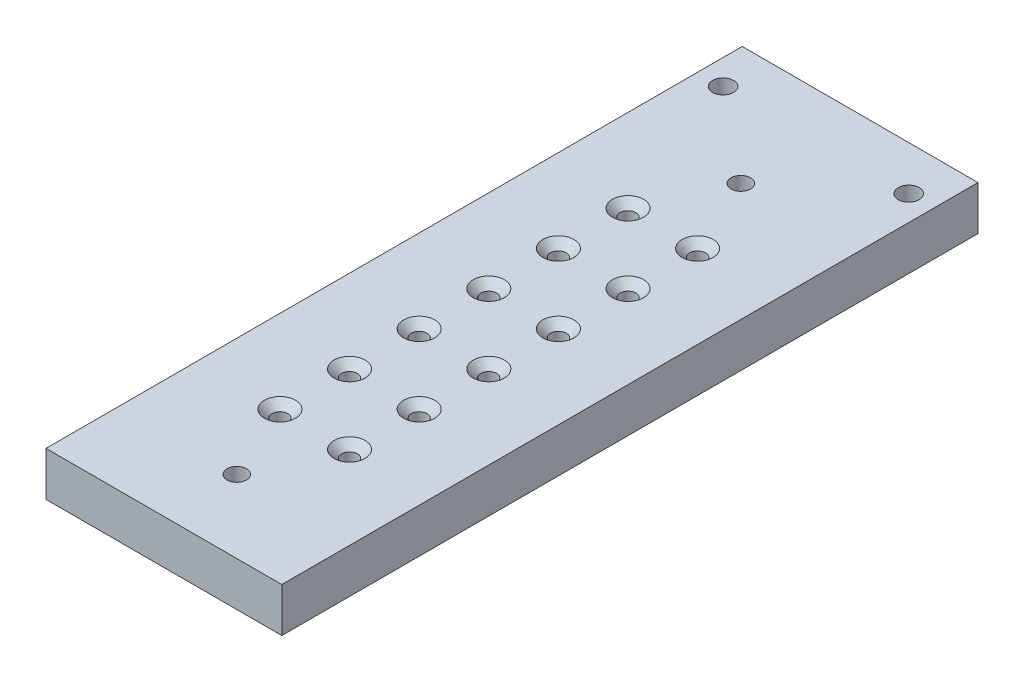
SolidWorks part; units mm, degrees
ref_plane "Front" through (0, 0, 0) normal (0, 0, 1) x (1, 0, 0)
ref_plane "Top" through (0, 0, 0) normal (0, 1, 0) x (1, 0, 0)
ref_plane "Right" through (0, 0, 0) normal (1, 0, 0) x (0, 0, -1)
sketch "Sketch1" plane through (0, 0, 0) normal (0, 0, 1) x (1, 0, 0)
  line L1 (-25.4, -4.7625) -> (25.4, -4.7625)
  line L2 (-25.4, -4.7625) -> (-25.4, 4.7625)
  line L3 (-25.4, 4.7625) -> (25.4, 4.7625)
  line L4 (25.4, -4.7625) -> (25.4, 4.7625)
  line L5 (-25.4, -4.7625) -> (25.4, 4.7625) construction
  line L6 (-25.4, 4.7625) -> (25.4, -4.7625) construction
  point P0 (0, 0)
  dimension "D1" = 50.8
  dimension "D2" = 9.525
extrude "Boss-Extrude1" add sketch "Sketch1" along normal mid plane 150
sketch "Sketch5" plane through (0, 4.7625, 0) normal (0, 1, 0) x (1, 0, 0)
  line L0 (-25.4, -75) -> (-25.4, 75) construction
  line L1 (-21.3194, 50) -> (21.3194, 50)
  line L2 (-21.3194, 50) -> (-21.3194, -60)
  line L3 (-21.3194, -60) -> (21.3194, -60)
  line L4 (21.3194, 50) -> (21.3194, -60)
  line L5 (-25.4, 45.8) -> (25.4, 45.8)
  line L6 (-25.4, 45.8) -> (-25.4, -55.8)
  line L7 (-25.4, -55.8) -> (25.4, -55.8)
  line L8 (25.4, 45.8) -> (25.4, -55.8)
  line L9 (25.4, -75) -> (25.4, 75) construction
  line L10 (25.4, -75) -> (-25.4, -75) construction
  line L12 (-9.525, -55.8) -> (9.525, -55.8)
  line L13 (-9.525, -55.8) -> (-9.525, -70.8)
  line L14 (-9.525, -70.8) -> (9.525, -70.8)
  line L15 (9.525, -55.8) -> (9.525, -70.8)
  line L16 (-25.4, 75) -> (25.4, 75)
  line L17 (-25.4, 75) -> (-25.4, 55.95)
  line L18 (-25.4, 55.95) -> (25.4, 55.95)
  line L19 (25.4, 75) -> (25.4, 55.95)
  point P12 (0, 50)
  point P13 (0, -55.8)
  point P15 (-21.3194, -5)
  point P16 (-25.4, -5)
  point P17 (0, -70.8)
  dimension "D1" = 110
  dimension "D2" = 101.6
  dimension "D3" = 15
  dimension "D4" = 15
  dimension "D5" = 19.05
  dimension "D6" = 19.05
hole_wizard "Tap Drill for M5x0.8 Tap1" positions "Sketch6" profile "Sketch7" hole size "M5x0.8" standard "ANSI Metric" end condition up to next
sketch "Sketch6" plane through (0, 4.7625, 0) normal (0, 1, 0) x (1, 0, 0)
  line L0 (-25.4, -55.8) -> (25.4, -55.8) construction
  line L1 (-25.4, 45.8) -> (25.4, 45.8) construction
  point P0 (0, -59.3)
  point P7 (0, 49.3)
  dimension "D1" = 3.5
  dimension "D2" = 3.5
sketch "Sketch7" plane through (0, 4.7625, 59.3) normal (1, 0, 0) x (0, 0, 1)
  line L0 (0, 0) -> (0, 9.525)
  line L1 (0, 9.525) -> (2.1, 9.525)
  line L2 (2.1, 9.525) -> (2.1, 0)
  line L5 (2.1, 0) -> (0, 0)
  line L11 (0, -6.35) -> (0, 107.95) construction
  dimension "Thru Hole Dia." = 4.2
  dimension "Thru Hole Depth" = 9.525
hole_wizard "M4 Clearance Hole1" positions "Sketch8" profile "Sketch9" hole size "M4" standard "ANSI Metric" end condition up to next
sketch "Sketch8" plane through (0, 4.7625, 0) normal (0, 1, 0) x (1, 0, 0)
  line L3 (20, 65.475) -> (-20, 65.475)
  line L5 (-25.4, 75) -> (25.4, 75) construction
  point P0 (-20, 65.475)
  point P2 (20, 65.475)
  point P17 (0, 65.475)
  dimension "D1" = 40
  dimension "D2" = 9.525
sketch "Sketch9" plane through (-20, 4.7625, -65.475) normal (1, 0, 0) x (0, 0, 1)
  line L0 (0, 0) -> (0, 9.525)
  line L1 (0, 9.525) -> (2.25, 9.525)
  line L2 (2.25, 9.525) -> (2.25, 0)
  line L5 (2.25, 0) -> (0, 0)
  line L11 (0, -6.35) -> (0, 107.95) construction
  dimension "Thru Hole Dia." = 4.5
  dimension "Thru Hole Depth" = 9.525
hole_wizard "CSK for M3 SFHCS1" positions "Sketch10" profile "Sketch11" countersink size "M3" standard "ANSI Metric" end condition through all
sketch "Sketch10" plane through (0, 4.7625, 0) normal (0, 1, 0) x (1, 0, 0)
  line L0 (7.5, 32.5) -> (-7.5, 32.5)
  line L1 (-21.3194, 50) -> (21.3194, 50) construction
  point P0 (7.5, 32.5)
  point P2 (-7.5, 32.5)
  point P9 (0, 32.5)
  dimension "D1" = 15
  dimension "D2" = 17.5
sketch "Sketch11" plane through (7.5, 4.7625, -32.5) normal (1, 0, 0) x (0, 0, 1)
  line L0 (0, 0) -> (0, 9.525)
  line L1 (0, 9.525) -> (1.7, 9.525)
  line L2 (1.7, 9.525) -> (1.7, 1.66)
  line L3 (1.7, 1.66) -> (3.36, 0)
  line L5 (3.36, 0) -> (0, 0)
  line L6 (-1.7, 1.66) -> (-3.36, 0) construction
  line L11 (0, -6.35) -> (0, 107.95) construction
  dimension "Thru Hole Dia." = 3.4
  dimension "Thru Hole Depth" = 9.525
  dimension "Near C'Sink Dia." = 6.72
  dimension "Near C'Sink Angle" = 90
pattern_linear "LPattern1" count 6 spacing 15 along (0, 0, 1) of "CSK for M3 SFHCS1"
